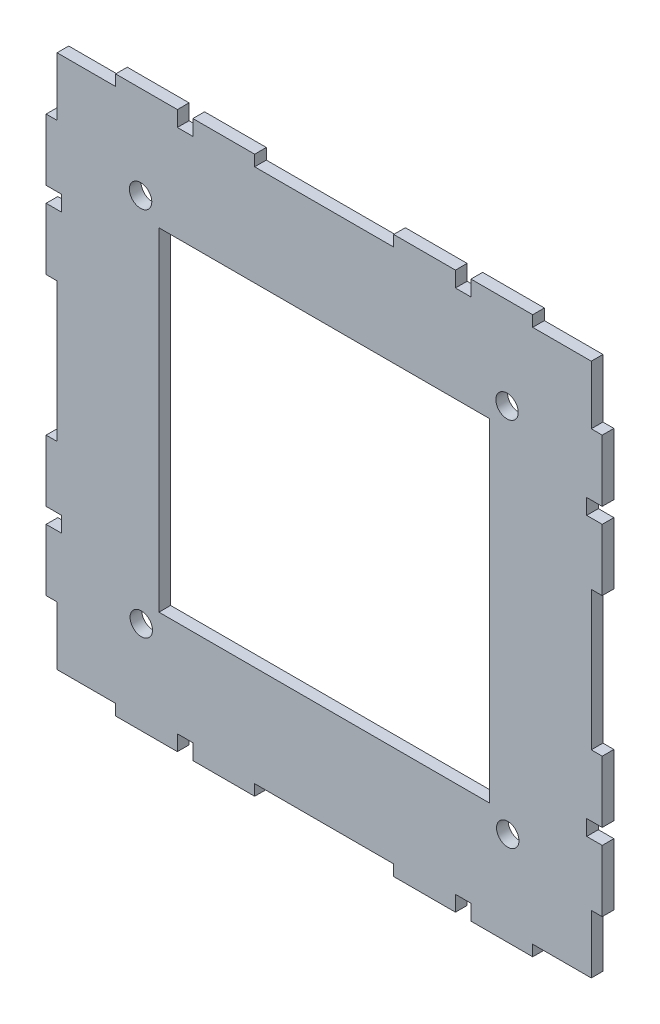
SolidWorks part; units mm, degrees
ref_plane "Front Plane" through (0, 0, 0) normal (0, 0, 1) x (1, 0, 0)
ref_plane "Top Plane" through (0, 0, 0) normal (0, 1, 0) x (1, 0, 0)
ref_plane "Right Plane" through (0, 0, 0) normal (1, 0, 0) x (0, 0, -1)
sketch "Sketch1" plane through (0, 0, 0) normal (0, 0, 1) x (1, 0, 0)
  line L0 (339.5169, 278.2937) -> (339.5169, 187.6474)
  line L1 (339.5169, 187.6474) -> (429.49, 187.6474)
  line L2 (429.49, 278.2937) -> (429.49, 187.6474)
  line L3 (339.5169, 278.2937) -> (429.49, 278.2937)
  line L548 (311.7757, 305.6983) -> (311.7757, 289.7519)
  line L549 (311.7757, 289.7519) -> (308.795, 289.7519)
  line L550 (308.795, 289.7519) -> (308.795, 272.9361)
  line L551 (308.795, 272.9361) -> (313.0176, 272.9361)
  line L552 (313.0176, 272.9361) -> (313.0176, 270.8248)
  line L553 (313.0176, 270.8248) -> (313.0176, 268.7135)
  line L554 (313.0176, 268.7135) -> (308.795, 268.7135)
  line L555 (308.795, 268.7135) -> (308.795, 251.8977)
  line L556 (308.795, 251.8977) -> (311.7757, 251.8977)
  line L557 (311.7757, 251.8977) -> (311.7757, 214.0435)
  line L558 (311.7757, 214.0435) -> (308.795, 214.0435)
  line L559 (308.795, 214.0435) -> (308.795, 197.2276)
  line L560 (308.795, 197.2276) -> (313.0176, 197.2276)
  line L561 (313.0176, 197.2276) -> (313.0176, 195.1163)
  line L562 (313.0176, 195.1163) -> (313.0176, 193.0051)
  line L563 (313.0176, 193.0051) -> (308.795, 193.0051)
  line L564 (308.795, 193.0051) -> (308.795, 176.1892)
  line L565 (308.795, 176.1892) -> (311.7757, 176.1892)
  line L566 (311.7757, 176.1892) -> (311.7757, 160.2428)
  line L567 (311.7757, 160.2428) -> (327.7221, 160.2428)
  line L568 (327.7221, 160.2428) -> (327.7221, 157.2621)
  line L569 (327.7221, 157.2621) -> (344.5379, 157.2621)
  line L570 (344.5379, 157.2621) -> (344.5379, 161.4847)
  line L571 (344.5379, 161.4847) -> (346.6492, 161.4847)
  line L572 (346.6492, 161.4847) -> (348.7605, 161.4847)
  line L573 (348.7605, 161.4847) -> (348.7605, 157.2621)
  line L574 (348.7605, 157.2621) -> (365.5763, 157.2621)
  line L575 (365.5763, 157.2621) -> (365.5763, 160.2428)
  line L576 (365.5763, 160.2428) -> (403.4305, 160.2428)
  line L577 (403.4305, 160.2428) -> (403.4305, 157.2621)
  line L578 (403.4305, 157.2621) -> (420.2464, 157.2621)
  line L579 (420.2464, 157.2621) -> (420.2464, 161.4847)
  line L580 (420.2464, 161.4847) -> (422.3576, 161.4847)
  line L581 (422.3576, 161.4847) -> (424.4689, 161.4847)
  line L582 (424.4689, 161.4847) -> (424.4689, 157.2621)
  line L583 (424.4689, 157.2621) -> (441.2848, 157.2621)
  line L584 (441.2848, 157.2621) -> (441.2848, 160.2428)
  line L585 (441.2848, 160.2428) -> (457.2312, 160.2428)
  line L586 (457.2312, 160.2428) -> (457.2312, 176.1892)
  line L587 (457.2312, 176.1892) -> (460.2119, 176.1892)
  line L588 (460.2119, 176.1892) -> (460.2119, 193.0051)
  line L589 (460.2119, 193.0051) -> (455.9893, 193.0051)
  line L590 (455.9893, 193.0051) -> (455.9893, 195.1163)
  line L591 (455.9893, 195.1163) -> (455.9893, 197.2276)
  line L592 (455.9893, 197.2276) -> (460.2119, 197.2276)
  line L593 (460.2119, 197.2276) -> (460.2119, 214.0435)
  line L594 (460.2119, 214.0435) -> (457.2312, 214.0435)
  line L595 (457.2312, 214.0435) -> (457.2312, 251.8977)
  line L596 (457.2312, 251.8977) -> (460.2119, 251.8977)
  line L597 (460.2119, 251.8977) -> (460.2119, 268.7135)
  line L598 (460.2119, 268.7135) -> (455.9893, 268.7135)
  line L599 (455.9893, 268.7135) -> (455.9893, 270.8248)
  line L600 (455.9893, 270.8248) -> (455.9893, 272.9361)
  line L601 (455.9893, 272.9361) -> (460.2119, 272.9361)
  line L602 (460.2119, 272.9361) -> (460.2119, 289.7519)
  line L603 (460.2119, 289.7519) -> (457.2312, 289.7519)
  line L604 (457.2312, 289.7519) -> (457.2312, 305.6983)
  line L605 (457.2312, 305.6983) -> (441.2848, 305.6983)
  line L606 (441.2848, 305.6983) -> (441.2848, 308.679)
  line L607 (441.2848, 308.679) -> (424.4689, 308.679)
  line L608 (424.4689, 308.679) -> (424.4689, 304.4564)
  line L609 (424.4689, 304.4564) -> (422.3576, 304.4564)
  line L610 (422.3576, 304.4564) -> (420.2464, 304.4564)
  line L611 (420.2464, 304.4564) -> (420.2464, 308.679)
  line L612 (420.2464, 308.679) -> (403.4305, 308.679)
  line L613 (403.4305, 308.679) -> (403.4305, 305.6983)
  line L614 (403.4305, 305.6983) -> (365.5763, 305.6983)
  line L615 (365.5763, 305.6983) -> (365.5763, 308.679)
  line L616 (365.5763, 308.679) -> (348.7605, 308.679)
  line L617 (348.7605, 308.679) -> (348.7605, 304.4564)
  line L618 (348.7605, 304.4564) -> (346.6492, 304.4564)
  line L619 (346.6492, 304.4564) -> (344.5379, 304.4564)
  line L620 (344.5379, 304.4564) -> (344.5379, 308.679)
  line L621 (344.5379, 308.679) -> (327.7221, 308.679)
  line L622 (327.7221, 308.679) -> (327.7221, 305.6983)
  line L623 (327.7221, 305.6983) -> (311.7757, 305.6983)
  line L627 (311.7757, 232.9706) -> (457.2312, 232.9706) construction
  line L632 (384.5034, 305.6983) -> (384.5034, 160.2428) construction
  circle A20 centre (334.5169, 283.4116) radius 3.05
  circle A21 centre (434.3024, 283.6553) radius 3.05
  circle A22 centre (434.49, 182.7653) radius 3.05
  circle A23 centre (334.7047, 182.5178) radius 3.05
extrude "Boss-Extrude1" add sketch "Sketch1" along normal blind 3.175
